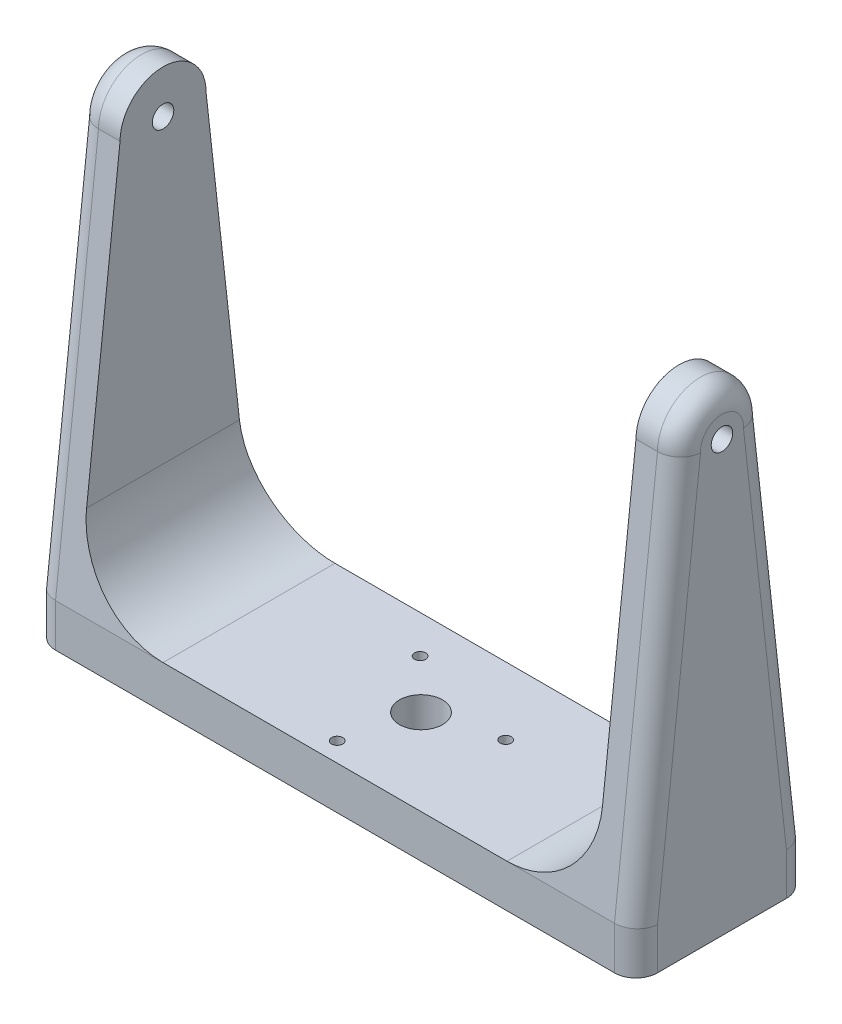
SolidWorks part; units mm, degrees
material "Polylactic Acid (PLA)"
ref_plane "Front Plane" through (0, 0, 0) normal (0, 0, 1) x (1, 0, 0)
ref_plane "Top Plane" through (0, 0, 0) normal (0, 1, 0) x (1, 0, 0)
ref_plane "Right Plane" through (0, 0, 0) normal (1, 0, 0) x (0, 0, -1)
sketch "Sketch1" plane through (0, 0, 0) normal (1, 0, 0) x (0, 0, -1)
  line L0 (0, 55) -> (0, -55) construction
  line L1 (55, 0) -> (-55, 0) construction
  line L2 (-20, 0) -> (20, 0)
  line L3 (-20, 0) -> (-20, 10)
  line L5 (20, 0) -> (20, 10)
  line L6 (-10, 100) -> (-20, 10)
  line L7 (10, 100) -> (20, 10)
  arc A0 (10, 100) -> (-10, 100) centre (0, 100) ccw
  circle A1 centre (0, 100) radius 2.5
  dimension "D1" = 20
  dimension "D5" = 5
  dimension "D2" = 100
  dimension "D3" = 40
  dimension "D4" = 20
extrude "Boss-Extrude1" add sketch "Sketch1" along normal mid plane 140
sketch "Sketch2" plane through (0, 0, 0) normal (0, -1, 0) x (1, 0, 0)
  line L0 (0, -55) -> (0, 55) construction
  line L1 (-60, 20) -> (60, 20)
  line L2 (-60, 20) -> (-60, -20)
  line L3 (-60, -20) -> (60, -20)
  line L4 (60, 20) -> (60, -20)
  dimension "D1" = 120
  dimension "D2" = 60
extrude "Cut-Extrude1" cut sketch "Sketch2" against normal blind 110 from offset 10 offset against normal yes
sketch "Sketch3" plane through (0, 0, 0) normal (0, -1, 0) x (1, 0, 0)
  line L0 (70, 20) -> (-70, 20) construction
  line L1 (0, 0) -> (-4, 15.4919) construction
  line L2 (0, 0) -> (15.4164, -4.2819) construction
  line L3 (0, -22) -> (0, 22) construction
  circle A0 centre (-4, 15.4919) radius 1.3
  circle A1 centre (15.4164, -4.2819) radius 1.3
  circle A2 centre (-11.4164, -11.2101) radius 1.3
  circle A3 centre (0, 0) radius 5
  dimension "D1" = 3
  dimension "D3" = 2.6
  dimension "D7" = 10
  dimension "D2" = 120
  dimension "D4" = 20
  dimension "D5" = 4
  dimension "D6" = 16
extrude "Cut-Extrude2" cut sketch "Sketch3" against normal up to surface (10 mm away) up to face at (0, 10, 0)
fillet "Fillet1" radius 5 10 edges at (70, 5, -20) (70, 5, 20) (-70, 5, 20) (-70, 5, -20) (-70, 55, -15) (-70, 55, 15) (-70, 110, 0) (70, 110, 0) (70, 55, -15) (70, 55, 15)
fillet "Fillet2" radius 20 2 edges at (-60, 10, 0) (60, 10, 0)
